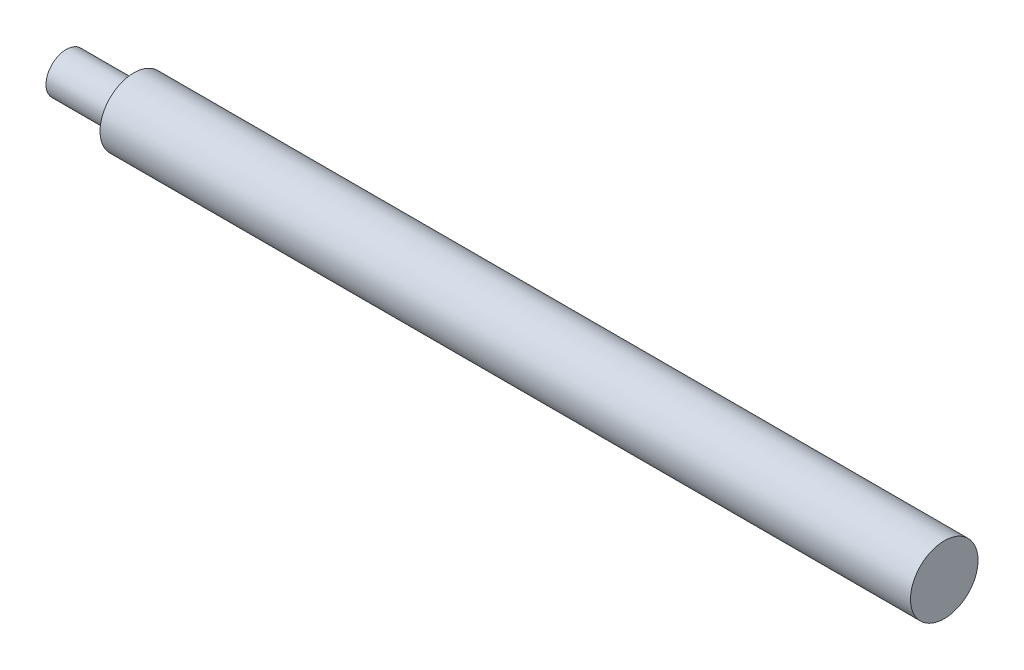
SolidWorks part; units mm, degrees
ref_plane "Plan de face" through (0, 0, 0) normal (0, 0, 1) x (1, 0, 0)
ref_plane "Plan de dessus" through (0, 0, 0) normal (0, 1, 0) x (1, 0, 0)
ref_plane "Plan de droite" through (0, 0, 0) normal (1, 0, 0) x (0, 0, -1)
sketch "Esquisse1" plane through (0, 0, 0) normal (0, 0, 1) x (1, 0, 0)
  line L0 (-55.2921, 0) -> (74.7079, 0)
  line L1 (74.7079, 0) -> (74.7079, 5)
  line L2 (74.7079, 5) -> (-45.2921, 5)
  line L3 (-45.2921, 5) -> (-45.2921, 3)
  line L4 (-45.2921, 3) -> (-55.2921, 3)
  line L5 (-55.2921, 3) -> (-55.2921, 0)
  dimension "D1" = 3
  dimension "D2" = 10
  dimension "D3" = 5
  dimension "D4" = 130
revolve "Révolution1" add sketch "Esquisse1" angle 360 about L0
